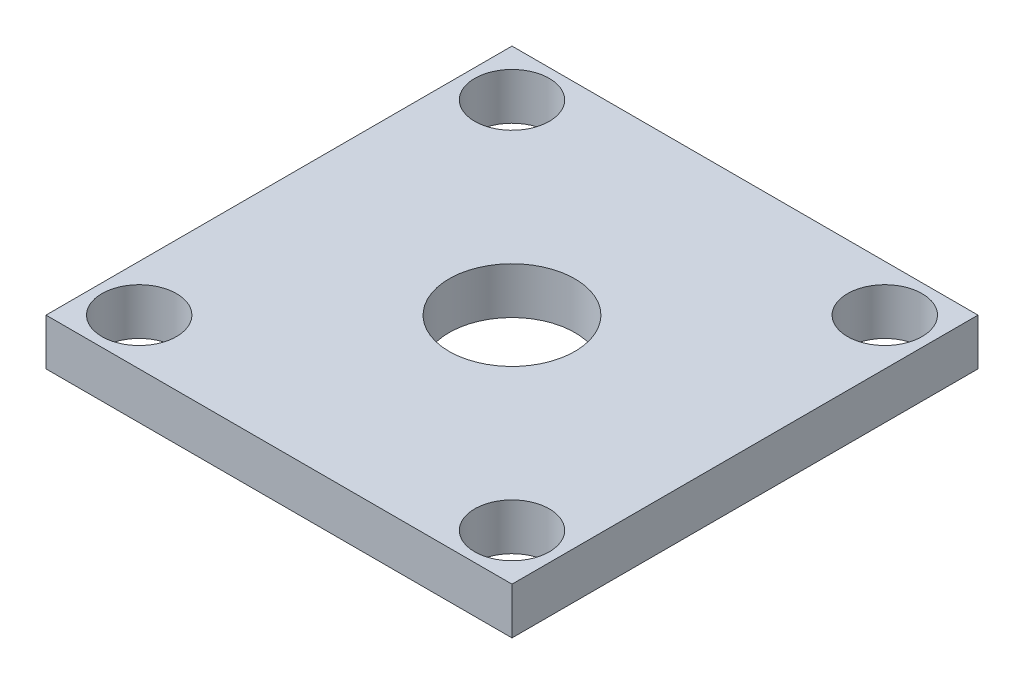
SolidWorks part; units mm, degrees
ref_plane "前视基准面" through (0, 0, 0) normal (0, 0, 1) x (1, 0, 0)
ref_plane "上视基准面" through (0, 0, 0) normal (0, 1, 0) x (1, 0, 0)
ref_plane "右视基准面" through (0, 0, 0) normal (1, 0, 0) x (0, 0, -1)
other "Configuration Table"
sketch "草图1" plane through (0, 0, 0) normal (0, 1, 0) x (1, 0, 0)
  line L0 (-5, 5) -> (-3, 3)
  line L1 (-5, 5) -> (5, 5)
  line L2 (-5, 5) -> (-5, -5)
  line L3 (-5, -5) -> (5, -5)
  line L4 (5, 5) -> (5, -5)
  line L5 (-5, 5) -> (5, -5) construction
  line L6 (-5, -5) -> (5, 5) construction
  line L7 (-3, 3) -> (3, 3)
  line L8 (-3, 3) -> (-3, -3)
  line L9 (-3, -3) -> (3, -3)
  line L10 (3, 3) -> (3, -3)
  line L11 (-3, 3) -> (3, -3) construction
  line L12 (-3, -3) -> (3, 3) construction
  line L13 (3, -3) -> (5, -5)
  circle A0 centre (0, 0) radius 1.35
  circle A1 centre (-4, 4) radius 0.8
  circle A2 centre (4, -4) radius 0.8
  circle A3 centre (4, 4) radius 0.8
  circle A4 centre (-4, -4) radius 0.8
  point P0 (0, 0)
  point P5 (0, 0)
  dimension "D1" = 2.7
  dimension "D4" = 1.6
  dimension "D2" = 6
  dimension "D3" = 10
  dimension "D5" = 1
  dimension "D6" = 1
extrude "凸台-拉伸1" add sketch "草图1" along normal blind 1 contours A2 L13 L4 L1 L0 A1 L7 L10 A3 | A2 L13 L9 L8 L0 A1 L2 L3 A4 | L10 L7 L8 L9 A0
